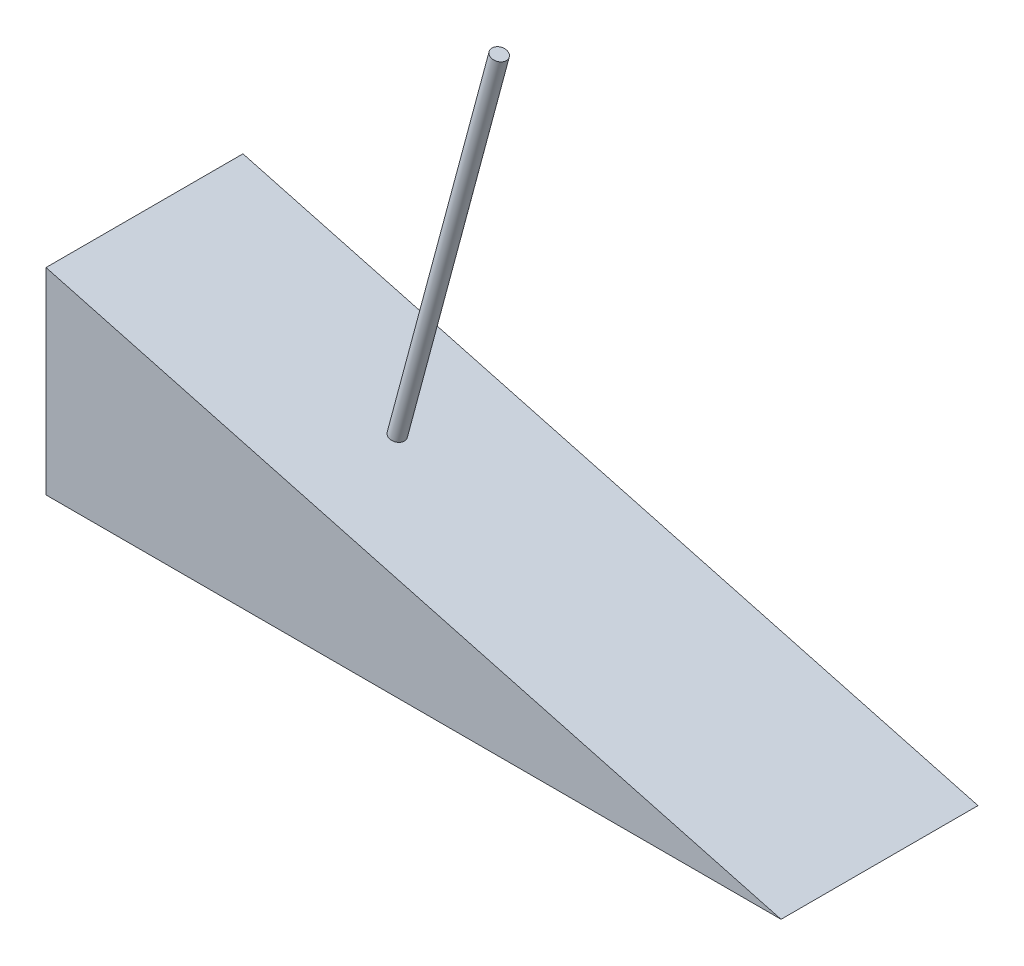
SolidWorks part; units mm, degrees
ref_plane "Front Plane" through (0, 0, 0) normal (0, 0, 1) x (1, 0, 0)
ref_plane "Top Plane" through (0, 0, 0) normal (0, 1, 0) x (1, 0, 0)
ref_plane "Right Plane" through (0, 0, 0) normal (1, 0, 0) x (0, 0, -1)
sketch "Sketch1" plane through (0, 0, 0) normal (0, 0, 1) x (1, 0, 0)
  line L0 (-22.1507, 20) -> (52.4903, 0)
  line L1 (52.4903, 0) -> (-22.1507, 0)
  line L2 (-22.1507, 0) -> (-22.1507, 20)
  point P4 (32.7989, 0)
  dimension "D1" = 15
  dimension "D2" = 20
extrude "Boss-Extrude1" add sketch "Sketch1" along normal blind 20
sketch "Sketch2" plane through (3.5162, 13.1226, 0) normal (0.2588, 0.9659, 0) x (0.9659, -0.2588, 0)
  line L0 (50.7018, 0) -> (-26.5723, 0) construction
  circle A0 centre (0, -10) radius 0.75
  dimension "D1" = 1.5
  dimension "D2" = 10
extrude "Boss-Extrude2" add sketch "Sketch2" along normal blind 40
